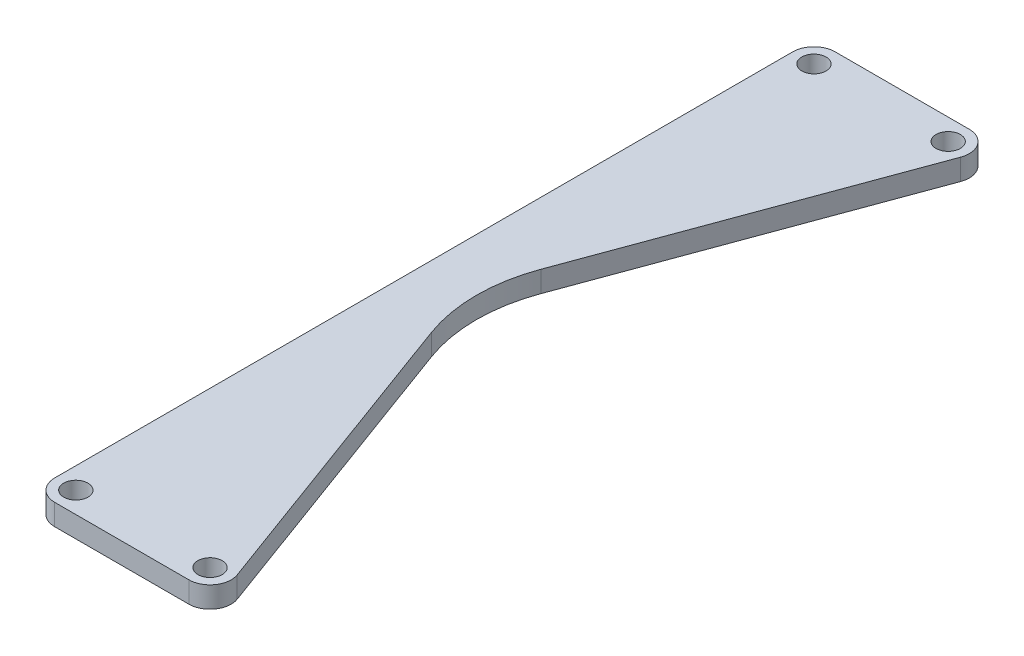
SolidWorks part; units mm, degrees
ref_plane "Front Plane" through (0, 0, 0) normal (0, 0, 1) x (1, 0, 0)
ref_plane "Top Plane" through (0, 0, 0) normal (0, 1, 0) x (1, 0, 0)
ref_plane "Right Plane" through (0, 0, 0) normal (1, 0, 0) x (0, 0, -1)
sketch "Sketch1" plane through (0, 0, 0) normal (0, 1, 0) x (1, 0, 0)
  line L0 (0, 0) -> (25.4, 0) construction
  line L1 (0, 0) -> (0, -139.7) construction
  line L2 (-4, -69.85) -> (4, -69.85) construction
  line L3 (-4, -143.7) -> (-4, 4)
  line L4 (-4, 4) -> (25.4, 4)
  line L5 (-4, -143.7) -> (25.4, -143.7)
  line L6 (4, -69.85) -> (29.1546, -1.3794)
  line L7 (4, -69.85) -> (29.1546, -138.3206)
  circle A0 centre (0, 0) radius 2.3
  circle A1 centre (25.4, 0) radius 2.3
  circle A2 centre (25.4, -139.7) radius 2.3
  circle A3 centre (0, -139.7) radius 2.3
  arc A4 (25.4, -143.7) -> (29.1546, -138.3206) centre (25.4, -139.7) ccw
  arc A5 (29.1546, -1.3794) -> (25.4, 4) centre (25.4, 0) ccw
  point P15 (0, -69.85)
  point P18 (-4, -69.85)
  dimension "D1" = 4.6
  dimension "D8" = 4
  dimension "D4" = 25.4
  dimension "D5" = 139.7
  dimension "D6" = 8
  dimension "D7" = 4
  dimension "D2" = 2
  dimension "D3" = 2
extrude "Boss-Extrude2" add sketch "Sketch1" along normal blind 4
fillet "Fillet1" radius 4 2 edges at (-4, 2, -4) (-4, 2, 143.7)
fillet "Fillet2" radius 30 1 edges at (4, 2, 69.85)
